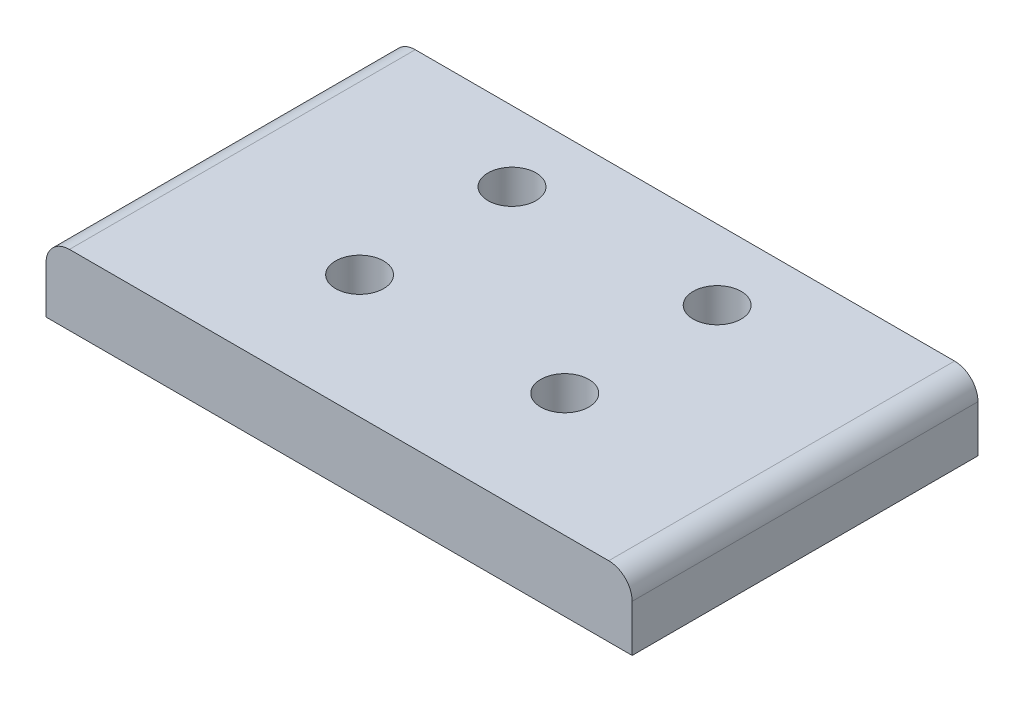
SolidWorks part; units mm, degrees
ref_plane "Front Plane" through (0, 0, 0) normal (0, 0, 1) x (1, 0, 0)
ref_plane "Top Plane" through (0, 0, 0) normal (0, 1, 0) x (1, 0, 0)
ref_plane "Right Plane" through (0, 0, 0) normal (1, 0, 0) x (0, 0, -1)
sketch "Sketch1" plane through (0, 0, 0) normal (0, 1, 0) x (1, 0, 0)
  line L0 (16.25, 0) -> (16.25, 29.5)
  line L1 (0, 0) -> (50, 0)
  line L2 (0, 0) -> (0, 29.5)
  line L3 (0, 29.5) -> (50, 29.5)
  line L4 (50, 0) -> (50, 29.5)
  line L5 (16.25, 10.5) -> (50, 10.5)
  line L6 (33.75, 0) -> (33.75, 29.5)
  line L7 (16.25, 23.5) -> (50, 23.5)
  dimension "D1" = 50
  dimension "D2" = 29.5
  dimension "D3" = 13
  dimension "D4" = 10.5
  dimension "D5" = 17.5
  dimension "D6" = 16.25
extrude "Boss-Extrude1" add sketch "Sketch1" along normal blind 6 contours L3 L2 L1 L0 | L0 L7 L6 L3 | L7 L0 L5 L6 | L7 L6 L5 L4 | L1 L6 L5 L0 | L6 L1 L4 L5 | L6 L7 L4 L3
fillet "Fillet1" radius 2 1 edges at (0, 6, -14.75)
fillet "Fillet2" radius 2 1 edges at (50, 6, -14.75)
sketch "Sketch4" plane through (0, 0, 0) normal (0, -1, 0) x (1, 0, 0)
  line L0 (33.75, 0) -> (33.75, -29.5) construction
  line L1 (16.25, -23.5) -> (33.75, -23.5)
  line L2 (16.25, -23.5) -> (16.25, -10.5)
  line L3 (16.25, -10.5) -> (33.75, -10.5)
  line L4 (33.75, -23.5) -> (33.75, -10.5)
  line L5 (16.25, -10.5) -> (50, -10.5) construction
  dimension "D1" = 0
  dimension "D2" = 0
hole_wizard "Ø4.0mm Dowel Hole2" positions "3DSketch3" profile "Sketch5" hole size "Ø4.0" standard "ANSI Metric" end condition through all
sketch3d "3DSketch3"
  point P0 (16.25, 0, -23.5)
  point P3 (33.75, 0, -23.5)
  point P6 (33.75, 0, -10.5)
  point P9 (16.25, 0, -10.5)
sketch "Sketch5" plane through (16.25, 0, -23.5) normal (1, 0, 0) x (0, 0, -1)
  line L0 (0, 0) -> (0, 6)
  line L1 (0, 6) -> (2.05, 6)
  line L2 (2.05, 6) -> (2.05, 0)
  line L5 (2.05, 0) -> (0, 0)
  line L11 (0, -6.35) -> (0, 107.95) construction
  dimension "Thru Hole Dia." = 4.1
  dimension "Thru Hole Depth" = 6
